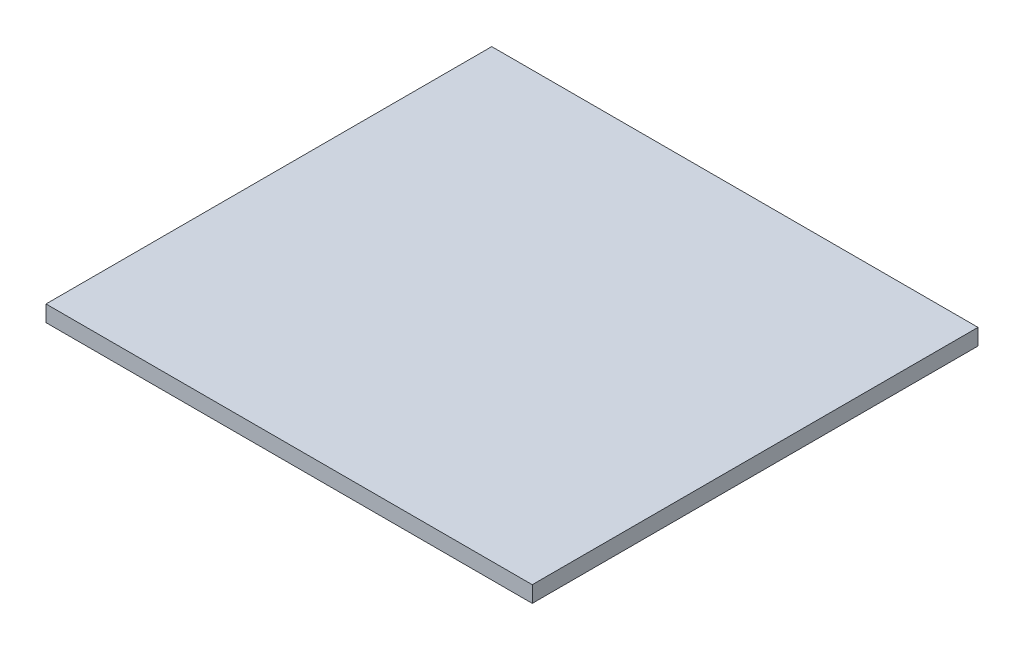
SolidWorks part; units mm, degrees
material "201 Annealed Stainless Steel (SS)"
ref_plane "Front Plane" through (0, 0, 0) normal (0, 0, 1) x (1, 0, 0)
ref_plane "Top Plane" through (0, 0, 0) normal (0, 1, 0) x (1, 0, 0)
ref_plane "Right Plane" through (0, 0, 0) normal (1, 0, 0) x (0, 0, -1)
sketch "Sketch1" plane through (0, 0, 0) normal (0, 1, 0) x (1, 0, 0)
  line L1 (-600, -550) -> (600, -550)
  line L2 (-600, -550) -> (-600, 550)
  line L3 (-600, 550) -> (600, 550)
  line L4 (600, -550) -> (600, 550)
  line L5 (-600, -550) -> (600, 550) construction
  line L6 (-600, 550) -> (600, -550) construction
  point P0 (0, 0)
  dimension "D1" = 1200
  dimension "D2" = 1100
extrude "Boss-Extrude1" add sketch "Sketch1" along normal blind 40
